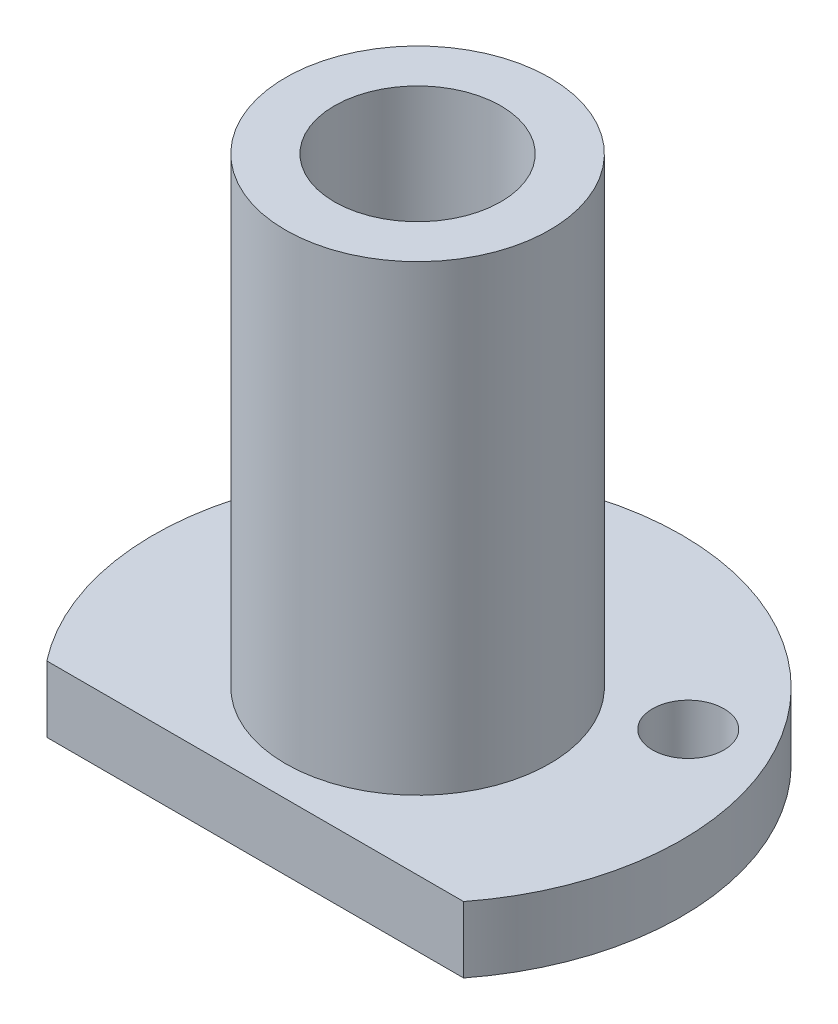
SolidWorks part; units mm, degrees
material "Delrin 2700 NC010, Low Viscosity Acetal Copolymer (SS)"
ref_plane "Front Plane" through (0, 0, 0) normal (0, 0, 1) x (1, 0, 0)
ref_plane "Top Plane" through (0, 0, 0) normal (0, 1, 0) x (1, 0, 0)
ref_plane "Right Plane" through (0, 0, 0) normal (1, 0, 0) x (0, 0, -1)
sketch "Sketch1" plane through (0, 0, 0) normal (0, 1, 0) x (1, 0, 0)
  circle A0 centre (0, 0) radius 19.05
  dimension "D1" = 38.1
extrude "Boss-Extrude1" add sketch "Sketch1" along normal blind 4.7752
sketch "Sketch2" plane through (0, 4.7752, 0) normal (0, 1, 0) x (1, 0, 0)
  circle A0 centre (0, 0) radius 9.525
  dimension "D1" = 19.05
extrude "Boss-Extrude2" add sketch "Sketch2" along normal blind 33.3248
sketch "Sketch3" plane through (0, 0, 0) normal (0, -1, 0) x (1, 0, 0)
  circle A0 centre (0, 0) radius 14.2875 construction
  circle A1 centre (0, 14.2875) radius 2.5781
  circle A2 centre (-12.3733, -7.1438) radius 2.5781
  circle A3 centre (12.3733, -7.1437) radius 2.5781
  point P12 (0, 0)
  dimension "D1" = 5.1562
  dimension "D2" = 28.575
  dimension "D3" = 3
extrude "Cut-Extrude1" cut sketch "Sketch3" against normal up to next
sketch "Sketch4" plane through (0, 0, 0) normal (0, -1, 0) x (1, 0, 0)
  circle A0 centre (0, 0) radius 6
  dimension "D1" = 12
extrude "Cut-Extrude2" cut sketch "Sketch4" against normal up to next
sketch "Sketch5" plane through (0, 0, 0) normal (0, -1, 0) x (-1, 0, 0)
  line L0 (15.0264, -11.7094) -> (-15.0264, -11.7094)
  line L1 (-12.3733, 7.1437) -> (12.3733, 7.1438) construction
  arc A0 (-15.0264, -11.7094) -> (15.0264, -11.7094) centre (0, 0) ccw
  dimension "D1" = 19.05
extrude "Cut-Extrude3" cut sketch "Sketch5" against normal up to next
